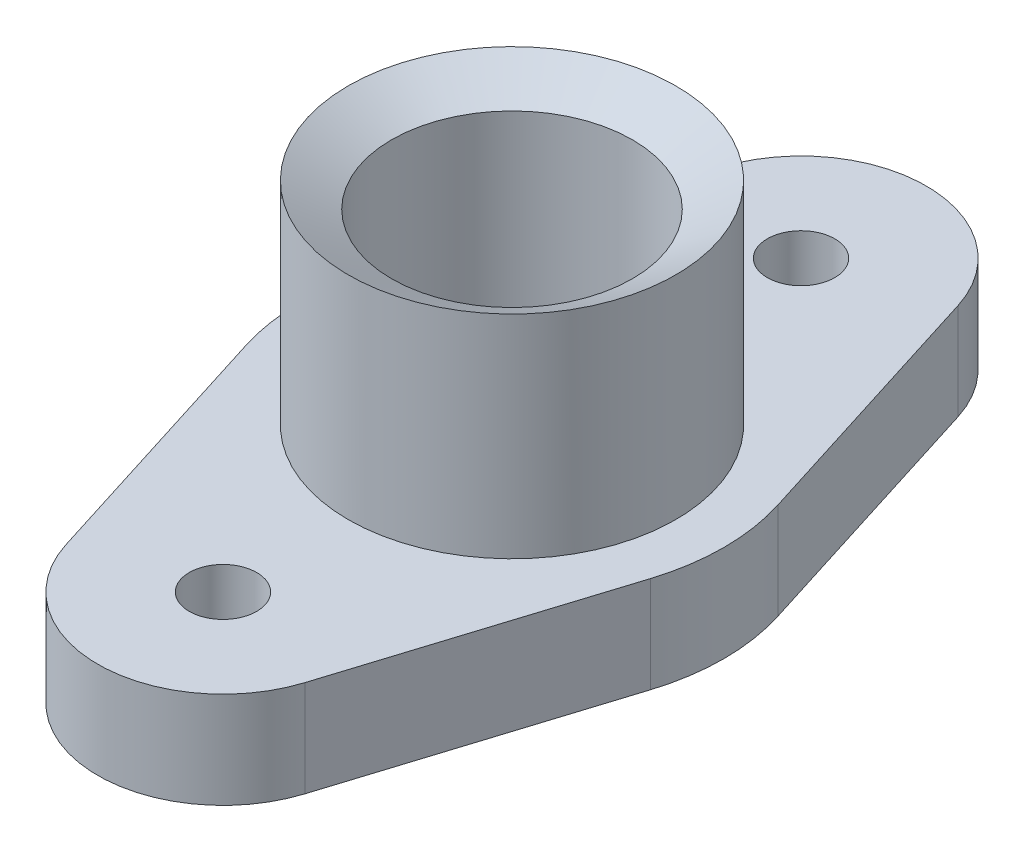
SolidWorks part; units mm, degrees
ref_plane "前视基准面" through (0, 0, 0) normal (0, 0, 1) x (1, 0, 0)
ref_plane "上视基准面" through (0, 0, 0) normal (0, 1, 0) x (1, 0, 0)
ref_plane "右视基准面" through (0, 0, 0) normal (1, 0, 0) x (0, 0, -1)
sketch "草图1" plane through (0, 0, 0) normal (0, 1, 0) x (1, 0, 0)
  line L0 (-12.4012, 33.9) -> (-20.9867, 6.6)
  line L1 (0, -30) -> (0, 30)
  line L2 (12.4012, 33.9) -> (20.9867, 6.6)
  line L3 (0, 0) -> (22.7848, 0) construction
  line L4 (12.4012, -33.9) -> (20.9867, -6.6)
  line L5 (-12.4012, -33.9) -> (-20.9867, -6.6)
  arc A0 (-20.9867, 6.6) -> (20.9867, 6.6) centre (0, 0) ccw
  arc A2 (12.4012, -33.9) -> (-12.4012, -33.9) centre (0, -30) cw
  arc A3 (12.4012, 33.9) -> (-12.4012, 33.9) centre (0, 30) ccw
  arc A4 (-20.9867, -6.6) -> (20.9867, -6.6) centre (0, 0) cw
  dimension "D1" = 44
  dimension "D2" = 13
  dimension "D3" = 30
extrude "凸台-拉伸1" add sketch "草图1" along normal blind 10
sketch "草图2" plane through (0, 10, 0) normal (0, 1, 0) x (1, 0, 0)
  circle A0 centre (0, 0) radius 17
  dimension "D1" = 34
extrude "凸台-拉伸2" add sketch "草图2" along normal blind 22
hole_wizard "大小mm 暗销孔1" positions "3D草图1" profile "草图3" hole size "Ø1.0" standard "GB" end condition through all
sketch3d "3D草图1"
  arc A0 (12.4012, 10, -33.9) -> (-12.4012, 10, -33.9) centre (0, 10, -30) ccw construction
  arc A1 (12.4012, 10, 33.9) -> (-12.4012, 10, 33.9) centre (0, 10, 30) ccw construction
  point P0 (0, 10, -30)
  point P2 (0, 10, 30)
  point P8 (0, 23, -30)
  point P9 (0, 0, 0)
  point P13 (0, -3, 30)
sketch "草图3" plane through (0, 10, -30) normal (1, 0, 0) x (0, 0, 1)
  line L0 (0, 0) -> (0, 10)
  line L1 (0, 10) -> (3.5, 10)
  line L2 (3.5, 10) -> (3.5, 0)
  line L5 (3.5, 0) -> (0, 0)
  line L11 (0, -6.35) -> (0, 107.95) construction
  dimension "通孔孔直径" = 7
  dimension "通孔孔深度" = 10
hole_wizard "大小mm 暗销孔2" positions "3D草图2" profile "草图4" hole size "Ø1.0" standard "GB" end condition through all
sketch3d "3D草图2"
  circle A0 centre (0, 32, 0) radius 17 construction
  point P0 (0, 32, 0)
  point P4 (0, 49, 0)
sketch "草图4" plane through (0, 32, 0) normal (1, 0, 0) x (0, 0, 1)
  line L0 (0, 0) -> (0, 32)
  line L1 (0, 32) -> (12.5, 32)
  line L2 (12.5, 32) -> (12.5, 0)
  line L5 (12.5, 0) -> (0, 0)
  line L11 (0, -6.35) -> (0, 107.95) construction
  dimension "通孔孔直径" = 25
  dimension "通孔孔深度" = 32
sketch "草图5" plane through (0, 0, 0) normal (0, 0, 1) x (1, 0, 0)
  line L0 (0, 32) -> (0, 0) construction
  line L1 (12.5, 32) -> (-12.5, 32) construction
  line L2 (0, 22.185) -> (17, 32)
  line L3 (17, 32) -> (17, 40.593)
  line L4 (17, 40.593) -> (0, 40.593)
  line L5 (0, 40.593) -> (0, 32) construction
  line L6 (0, 22.185) -> (0, 40.593)
  dimension "D1" = 60
  dimension "D2" = 8.593
revolve "切除-旋转1" cut sketch "草图5" angle 360 about L0
